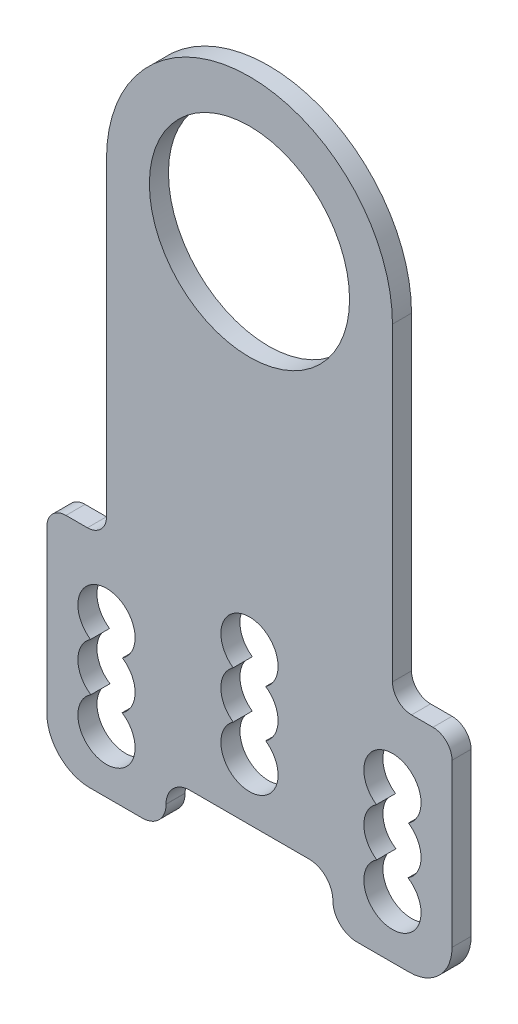
SolidWorks part; units mm, degrees
ref_plane "前视基准面" through (0, 0, 0) normal (0, 0, 1) x (1, 0, 0)
ref_plane "上视基准面" through (0, 0, 0) normal (0, 1, 0) x (1, 0, 0)
ref_plane "右视基准面" through (0, 0, 0) normal (1, 0, 0) x (0, 0, -1)
sketch "草图1" plane through (0, 0, 0) normal (0, 0, 1) x (1, 0, 0)
  line L0 (-15, 0) -> (-15, -32.5)
  line L1 (-17, -34.5) -> (-19.25, -34.5)
  line L2 (15, 0) -> (15, -32.5)
  line L3 (6.25, -52.9741) -> (-6.25, -52.9741)
  line L4 (16.75, -58) -> (11.25, -58)
  line L5 (21.25, -36.5) -> (21.25, -53.5)
  line L6 (17, -34.5) -> (19.25, -34.5)
  line L7 (-21.25, -36.5) -> (-21.25, -53.5)
  line L9 (-16.75, -58) -> (-11.25, -58)
  line L15 (-8.75, -55.4741) -> (-8.75, -55.5)
  line L16 (8.75, -55.4741) -> (8.75, -55.5)
  arc A0 (15, 0) -> (-15, 0) centre (0, 0) ccw
  arc A1 (-17, -34.5) -> (-15, -32.5) centre (-17, -32.5) ccw
  arc A2 (17, -34.5) -> (15, -32.5) centre (17, -32.5) cw
  arc A3 (-16.6386, -49.4871) -> (-13.3614, -49.4871) centre (-15, -52) ccw
  arc A4 (-16.6777, -44.4871) -> (-16.6386, -49.4871) centre (-15, -46.9741) ccw
  arc A5 (-13.3614, -49.4871) -> (-13.3223, -44.4871) centre (-15, -46.9741) ccw
  arc A6 (21.25, -36.5) -> (19.25, -34.5) centre (19.25, -36.5) ccw
  arc A7 (-19.25, -34.5) -> (-21.25, -36.5) centre (-19.25, -36.5) ccw
  circle A8 centre (0, 0) radius 10.5
  arc A9 (-1.7048, -39.5685) -> (-1.7048, -44.5056) centre (0, -42.0371) ccw
  arc A10 (-1.7048, -44.5056) -> (1.7048, -44.5056) centre (0, -46.9741) ccw
  arc A11 (-13.3223, -44.4871) -> (-16.6777, -44.4871) centre (-15, -42) ccw
  arc A14 (1.7048, -39.5685) -> (-1.7048, -39.5685) centre (0, -37.1) ccw
  arc A15 (1.7048, -44.5056) -> (1.7048, -39.5685) centre (0, -42.0371) ccw
  arc A20 (13.3614, -49.4871) -> (16.6386, -49.4871) centre (15, -52) ccw
  arc A21 (16.6386, -49.4871) -> (16.6777, -44.4871) centre (15, -46.9741) ccw
  arc A22 (16.6777, -44.4871) -> (13.3223, -44.4871) centre (15, -42) ccw
  arc A23 (13.3223, -44.4871) -> (13.3614, -49.4871) centre (15, -46.9741) ccw
  arc A29 (-11.25, -58) -> (-8.75, -55.5) centre (-11.25, -55.5) ccw
  arc A30 (-6.25, -52.9741) -> (-8.75, -55.4741) centre (-6.25, -55.4741) ccw
  arc A31 (8.75, -55.4741) -> (6.25, -52.9741) centre (6.25, -55.4741) ccw
  arc A32 (8.75, -55.5) -> (11.25, -58) centre (11.25, -55.5) ccw
  arc A33 (16.75, -58) -> (21.25, -53.5) centre (16.75, -53.5) ccw
  arc A43 (-21.25, -53.5) -> (-16.75, -58) centre (-16.75, -53.5) ccw
  dimension "D1" = 2
  dimension "D2" = 21
  dimension "D3" = 15
  dimension "D4" = 58
  dimension "D6" = 4.5
  dimension "D5" = 23.5
  dimension "D7" = 42.5
extrude "凸台-拉伸1" add sketch "草图1" along normal blind 2
